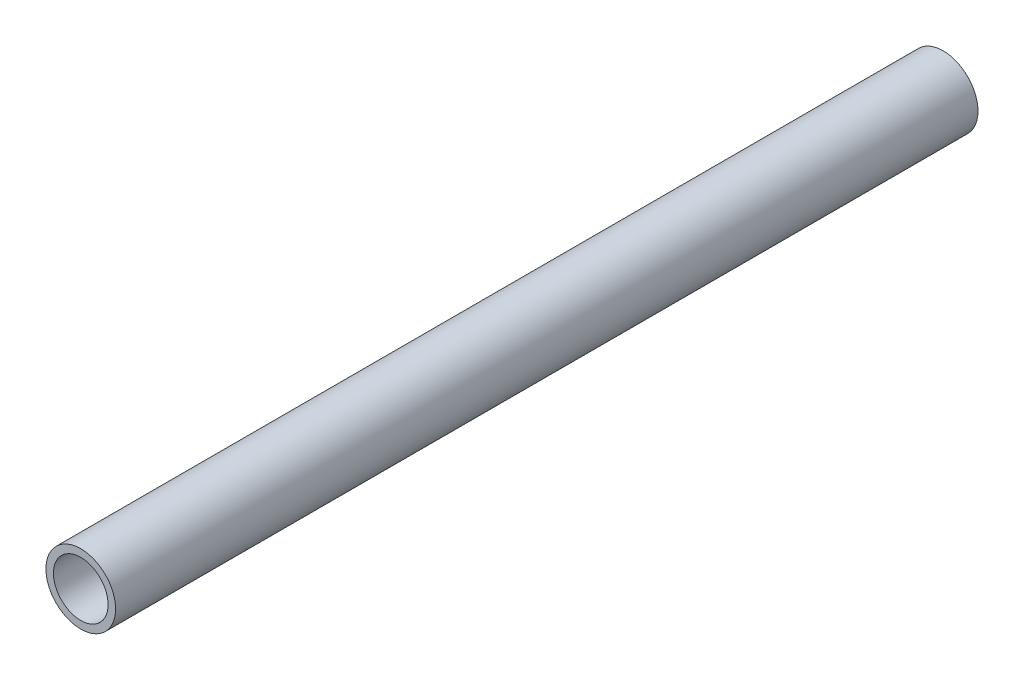
SolidWorks part; units mm, degrees
ref_plane "Front Plane" through (0, 0, 0) normal (0, 0, 1) x (1, 0, 0)
ref_plane "Top Plane" through (0, 0, 0) normal (0, 1, 0) x (1, 0, 0)
ref_plane "Right Plane" through (0, 0, 0) normal (1, 0, 0) x (0, 0, -1)
sketch "Sketch1" plane through (0, 0, 0) normal (0, 0, 1) x (1, 0, 0)
  circle A0 centre (0, 0) radius 10.4648
  circle A1 centre (0, 0) radius 13.335
  dimension "D1" = 2.8702
  dimension "D2" = 26.67
extrude "Boss-Extrude1" add sketch "Sketch1" along normal blind 330.2
